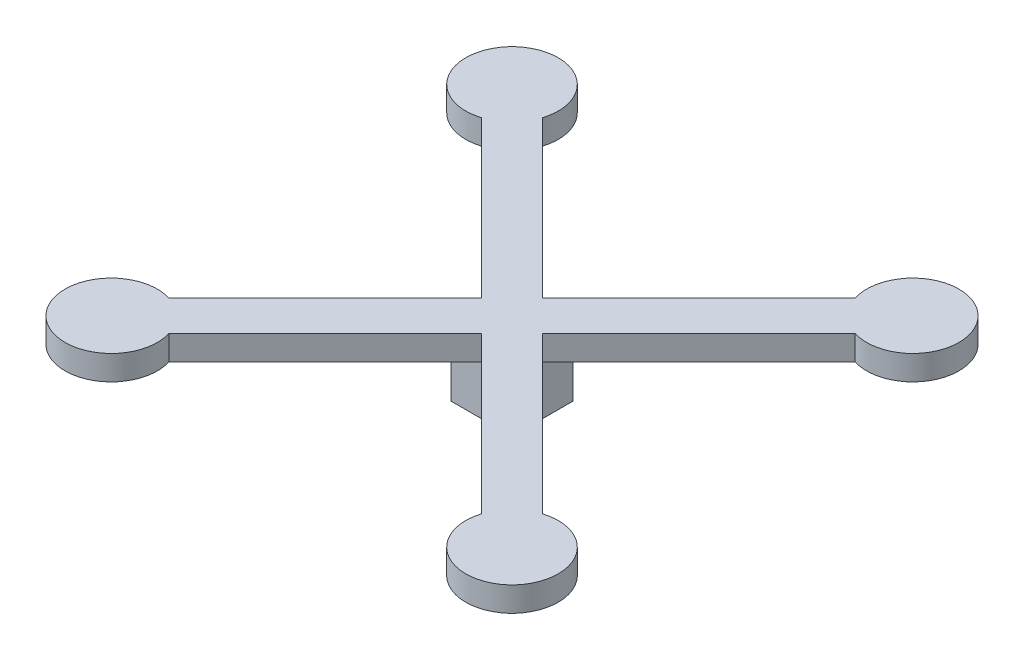
SolidWorks part; units mm, degrees
other "Camera1"
ref_plane "Front Plane" through (0, 0, 0) normal (0, 0, 1) x (1, 0, 0)
ref_plane "Top Plane" through (0, 0, 0) normal (0, 1, 0) x (1, 0, 0)
ref_plane "Right Plane" through (0, 0, 0) normal (1, 0, 0) x (0, 0, -1)
sketch "Sketch1" plane through (0, 0, 0) normal (0, 1, 0) x (1, 0, 0)
  line L0 (-12.3744, 12.3744) -> (12.3744, -12.3744)
  line L1 (12.3744, -12.3744) -> (175.0089, 150.2602)
  line L2 (175.0089, 150.2602) -> (150.2602, 175.0089)
  line L3 (150.2602, 175.0089) -> (-12.3744, 12.3744)
  line L4 (0, 0) -> (-70.3293, 0) construction
  line L5 (175.0089, -150.2602) -> (12.3744, 12.3744)
  line L6 (12.3744, 12.3744) -> (-12.3744, -12.3744)
  line L7 (-12.3744, -12.3744) -> (150.2602, -175.0089)
  line L8 (150.2602, -175.0089) -> (175.0089, -150.2602)
  line L9 (-150.2602, -175.0089) -> (12.3744, -12.3744)
  line L10 (12.3744, -12.3744) -> (-12.3744, 12.3744)
  line L11 (-12.3744, 12.3744) -> (-175.0089, -150.2602)
  line L12 (-175.0089, -150.2602) -> (-150.2602, -175.0089)
  line L13 (-175.0089, 150.2602) -> (-12.3744, -12.3744)
  line L14 (-12.3744, -12.3744) -> (12.3744, 12.3744)
  line L15 (12.3744, 12.3744) -> (-150.2602, 175.0089)
  line L16 (-150.2602, 175.0089) -> (-175.0089, 150.2602)
  circle A0 centre (162.6346, 162.6346) radius 37.5
  circle A1 centre (162.6346, -162.6346) radius 37.5
  circle A2 centre (-162.6346, -162.6346) radius 37.5
  circle A3 centre (-162.6346, 162.6346) radius 37.5
  point P4 (0, 0)
  point P31 (0, 0)
  dimension "D2" = 35
  dimension "D3" = 75
  dimension "D1" = 230
  dimension "D4" = 45
  dimension "D5" = 4
extrude "Boss-Extrude1" add sketch "Sketch1" along normal blind 20 contours L11 A2 L9 L12 | L9 A2 L11 L12 | A2 L9 L7 L13 L11 | L15 A3 L13 L16 | L13 A3 L15 L16 | A3 L13 L11 L3 L15 | A0 L3 L15 L5 L1 | L3 A0 L1 L2 | L1 A0 L3 L2 | A1 L5 L1 L9 L7 | L5 A1 L7 L8 | L7 A1 L5 L8 | L5 L6 L0 L1 | L7 L9 L0 L6 | L4 L0 L11 | L6 L15 L3 L0 | L6 L4 L13
sketch "Sketch2" plane through (0, 0, 0) normal (0, -1, 0) x (1, 0, 0)
  line L1 (-24.7487, 24.7487) -> (24.7487, 24.7487)
  line L2 (-24.7487, 24.7487) -> (-24.7487, -24.7487)
  line L3 (-24.7487, -24.7487) -> (24.7487, -24.7487)
  line L4 (24.7487, 24.7487) -> (24.7487, -24.7487)
  line L5 (-24.7487, 24.7487) -> (24.7487, -24.7487) construction
  line L6 (-24.7487, -24.7487) -> (24.7487, 24.7487) construction
  point P0 (0, 0)
extrude "Boss-Extrude2" add sketch "Sketch2" along normal blind 40
